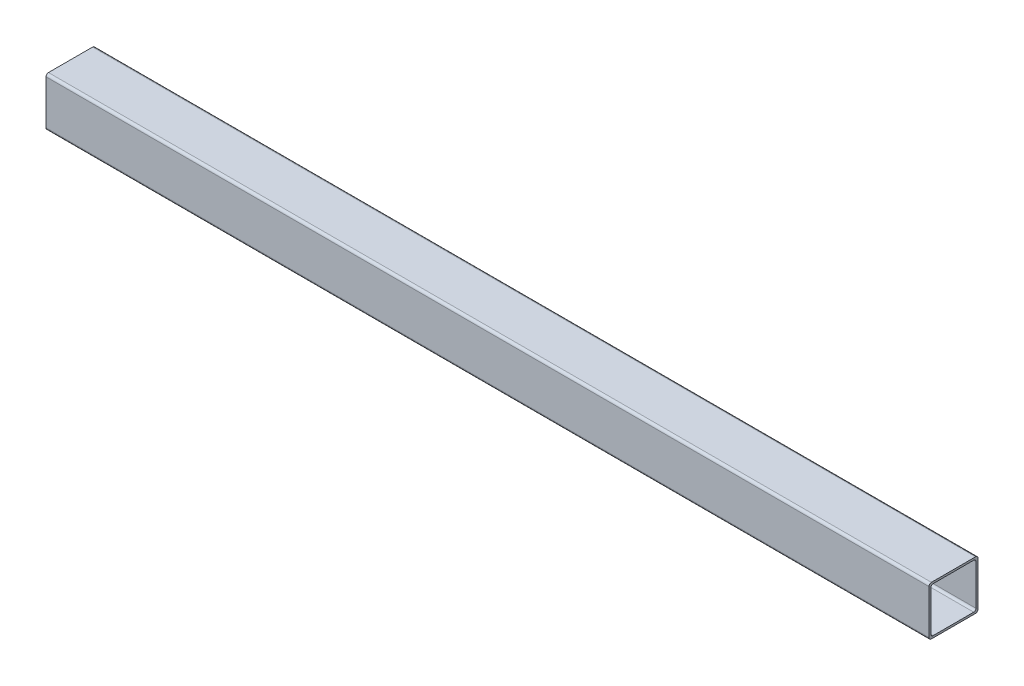
SolidWorks part; units mm, degrees
ref_plane "Front" through (0, 0, 0) normal (0, 0, 1) x (1, 0, 0)
ref_plane "Top" through (0, 0, 0) normal (0, 1, 0) x (1, 0, 0)
ref_plane "Right" through (0, 0, 0) normal (1, 0, 0) x (0, 0, -1)
sketch "Sketch1" plane through (0, 0, 0) normal (1, 0, 0) x (0, 0, -1)
  line L0 (-23.2918, 0) -> (-25.4, 0) construction
  line L1 (22.86, -25.4) -> (-22.86, -25.4) construction
  line L2 (25.4, -22.86) -> (25.4, 22.86) construction
  line L3 (22.86, 25.4) -> (-22.86, 25.4) construction
  line L4 (-25.4, -22.86) -> (-25.4, 22.86) construction
  line L5 (25.4, -25.4) -> (-25.4, 25.4) construction
  line L6 (25.4, 25.4) -> (-25.4, -25.4) construction
  line L7 (20.9626, 23.2918) -> (-20.9626, 23.2918) construction
  line L8 (23.2918, 20.9626) -> (23.2918, -20.9626) construction
  line L9 (20.9626, -23.2918) -> (-20.9626, -23.2918) construction
  line L10 (-23.2918, 20.9626) -> (-23.2918, -20.9626) construction
  line L11 (23.2918, 23.2918) -> (-23.2918, -23.2918) construction
  line L12 (23.2918, -23.2918) -> (-23.2918, 23.2918) construction
  line L13 (0, -23.2918) -> (0, -25.4) construction
  line L14 (23.2918, -20.9626) -> (23.2918, -25.4) construction
  line L15 (23.2918, 0) -> (25.4, 0) construction
  line L16 (23.2918, -25.4) -> (25.4, -25.4) construction
  arc A0 (-20.9626, -23.2918) -> (-23.2918, -20.9626) centre (-20.9626, -20.9626) cw construction
  arc A1 (23.2918, -20.9626) -> (20.9626, -23.2918) centre (20.9626, -20.9626) cw construction
  arc A2 (20.9626, 23.2918) -> (23.2918, 20.9626) centre (20.9626, 20.9626) cw construction
  arc A3 (-20.9626, 23.2918) -> (-23.2918, 20.9626) centre (-20.9626, 20.9626) ccw construction
  arc A4 (22.86, -25.4) -> (25.4, -22.86) centre (22.86, -22.86) ccw construction
  arc A5 (25.4, 22.86) -> (22.86, 25.4) centre (22.86, 22.86) ccw construction
  arc A6 (-22.86, 25.4) -> (-25.4, 22.86) centre (-22.86, 22.86) ccw construction
  arc A7 (-22.86, -25.4) -> (-25.4, -22.86) centre (-22.86, -22.86) cw construction
  point P0 (0, 0)
  point P6 (0, 0)
  dimension "D2" = 2.3292
  dimension "D3" = 2.54
  dimension "Outside Width" = 50.8
  dimension "Ouside Height" = 50.8
  dimension "Inside Height" = 46.5836
  dimension "Wall Thickness" = 2.1082
sketch "Sketch2" plane through (0, 0, 0) normal (0, 0, 1) x (1, 0, 0)
  line L0 (-457.2, 0) -> (457.2, 0) construction
  point P3 (-408.5082, 0)
  point P4 (408.5082, 0)
  dimension "Length" = 914.4
  dimension "D1" = 48.6918
  dimension "D2" = 48.6918
sketch "Sketch4" plane through (0, 0, 0) normal (1, 0, 0) x (0, 0, -1)
  line L8 (25.4, -22.86) -> (25.4, 22.86)
  line L9 (22.86, 25.4) -> (-22.86, 25.4)
  line L10 (-25.4, -22.86) -> (-25.4, 22.86)
  line L11 (22.86, -25.4) -> (-22.86, -25.4)
  line L12 (23.2918, 20.9626) -> (23.2918, -20.9626)
  line L13 (20.9626, -23.2918) -> (-20.9626, -23.2918)
  line L14 (-23.2918, 20.9626) -> (-23.2918, -20.9626)
  line L15 (20.9626, 23.2918) -> (-20.9626, 23.2918)
  arc A8 (25.4, 22.86) -> (22.86, 25.4) centre (22.86, 22.86) ccw
  arc A9 (-22.86, 25.4) -> (-25.4, 22.86) centre (-22.86, 22.86) ccw
  arc A10 (-25.4, -22.86) -> (-22.86, -25.4) centre (-22.86, -22.86) ccw
  arc A11 (22.86, -25.4) -> (25.4, -22.86) centre (22.86, -22.86) ccw
  arc A12 (20.9626, -23.2918) -> (23.2918, -20.9626) centre (20.9626, -20.9626) ccw
  arc A13 (-23.2918, -20.9626) -> (-20.9626, -23.2918) centre (-20.9626, -20.9626) ccw
  arc A14 (-20.9626, 23.2918) -> (-23.2918, 20.9626) centre (-20.9626, 20.9626) ccw
  arc A15 (23.2918, 20.9626) -> (20.9626, 23.2918) centre (20.9626, 20.9626) ccw
extrude "Boss-Extrude1" add sketch "Sketch4" along normal up to vertex (457.2 mm away) and the other way up to vertex (457.2 mm away)
equation "\"D3@Sketch1\"=\"Outside Width@Sketch1\"*.05"
equation "\"D2@Sketch1\" = \"Inside Height@Sketch1\" * .05"
equation "\"D1@Sketch2\"=\"Outside Width@Sketch1\"-\"Wall Thickness@Sketch1\""
equation "\"D2@Sketch2\"=\"D1@Sketch2\""
